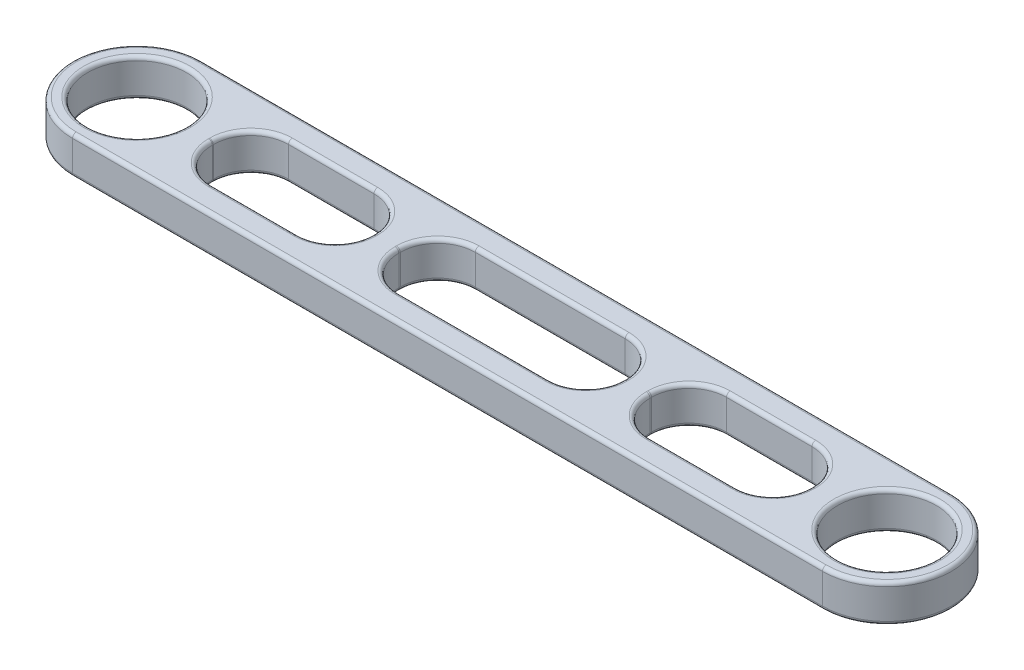
SolidWorks part; units mm, degrees
material "PA Type 6"
ref_plane "Plan de face" through (0, 0, 0) normal (0, 0, 1) x (1, 0, 0)
ref_plane "Plan de dessus" through (0, 0, 0) normal (0, 1, 0) x (1, 0, 0)
ref_plane "Plan de droite" through (0, 0, 0) normal (1, 0, 0) x (0, 0, -1)
sketch "Esquisse1" plane through (0, 0, 0) normal (0, 1, 0) x (1, 0, 0)
  line L3 (-50, 8.6) -> (50, 8.6)
  line L6 (-50, -8.6) -> (50, -8.6)
  line L8 (-50, -8.6) -> (50, 8.6) construction
  line L12 (0, 8.6) -> (0, -8.6) construction
  line L24 (-41.2822, 5.1) -> (-18.5, 5.1)
  line L25 (-18.5, 5.1) -> (-18.5, -5.1)
  line L26 (-18.5, -5.1) -> (-41.2822, -5.1)
  line L28 (-43.4, 0) -> (-39.9, 0) construction
  line L29 (41.2822, 5.1) -> (18.5, 5.1)
  line L30 (18.5, 5.1) -> (18.5, -5.1)
  line L31 (18.5, -5.1) -> (41.2822, -5.1)
  line L32 (43.4, 0) -> (39.9, 0) construction
  line L33 (-15, 5.1) -> (-15, -5.1)
  line L34 (-15, -5.1) -> (15, -5.1)
  line L35 (15, -5.1) -> (15, 5.1)
  line L36 (15, 5.1) -> (-15, 5.1)
  arc A4 (-50, 8.6) -> (-50, -8.6) centre (-50, 0) ccw
  circle A13 centre (-50, 0) radius 6.6
  arc A20 (50, -8.6) -> (50, 8.6) centre (50, 0) ccw
  circle A21 centre (50, 0) radius 6.6
  arc A22 (-41.2822, -5.1) -> (-41.2822, 5.1) centre (-50, 0) ccw
  arc A24 (41.2822, -5.1) -> (41.2822, 5.1) centre (50, 0) cw
  point P12 (0, 0)
  point P21 (-50, 0)
  point P24 (-50, 0)
  dimension "D5" = 13.2
  dimension "D9" = 13.2
  dimension "D2" = 8.6
  dimension "D10" = 3.5
  dimension "D11" = 3.5
  dimension "D13" = 100
  dimension "D14" = 3.5
  dimension "D12" = 3.5
  dimension "D15" = 3.5
  dimension "D16" = 30
extrude "Boss.-Extru.1" add sketch "Esquisse1" along normal blind 5
fillet "Congé3" radius 5 12 edges at (-18.5, 2.5, -5.1) (41.2822, 2.5, -5.1) (41.2822, 2.5, 5.1) (-18.5, 2.5, 5.1) (18.5, 2.5, 5.1) (18.5, 2.5, -5.1) (-41.2822, 2.5, -5.1) (-41.2822, 2.5, 5.1) (-15, 2.5, 5.1) (15, 2.5, -5.1) (15, 2.5, 5.1) (-15, 2.5, -5.1)
fillet "Congé2" radius 0.5 60 edges at (29.2002, 0, -5.1) (39.9, 0, 0) (29.2002, 0, 5.1) (18.5, 0, 0) (50, 0, 6.6) (-29.2002, 0, -5.1) (-18.5, 0, 0) (-29.2002, 0, 5.1) (-39.9, 0, 0) (58.6, 0, 0) (0, 0, -8.6) (-58.6, 0, 0) (0, 0, 8.6) (-50, 0, 6.6) (39.9, 5, 0) (29.2002, 5, -5.1) (18.5, 5, 0) (29.2002, 5, 5.1) (-50, 5, 6.6) (50, 5, 6.6) (-58.6, 5, 0) (0, 5, -8.6) (58.6, 5, 0) (0, 5, 8.6) (-18.5, 5, 0) (-29.2002, 5, -5.1) (-39.9, 5, 0) (-29.2002, 5, 5.1) (38.4476, 0, -3.6238) (38.4476, 0, 3.6238) (19.9645, 0, 3.6355) (19.9645, 0, -3.6355) (-19.9645, 0, -3.6355) (-19.9645, 0, 3.6355) (-38.4476, 0, 3.6238) (-38.4476, 0, -3.6238) (38.4476, 5, 3.6238) (38.4476, 5, -3.6238) (19.9645, 5, -3.6355) (19.9645, 5, 3.6355) (-19.9645, 5, 3.6355) (-19.9645, 5, -3.6355) (-38.4476, 5, -3.6238) (-38.4476, 5, 3.6238) (15, 0, 0) (0, 0, 5.1) (-15, 0, 0) (0, 0, -5.1) (0, 5, 5.1) (15, 5, 0) (0, 5, -5.1) (-15, 5, 0) (13.5355, 0, 3.6355) (-13.5355, 0, 3.6355) (-13.5355, 0, -3.6355) (13.5355, 0, -3.6355) (-13.5355, 5, 3.6355) (13.5355, 5, 3.6355) (13.5355, 5, -3.6355) (-13.5355, 5, -3.6355)
equation "\"D2@Esquisse1\"=\"D5@Esquisse1\"/2 + 2"
